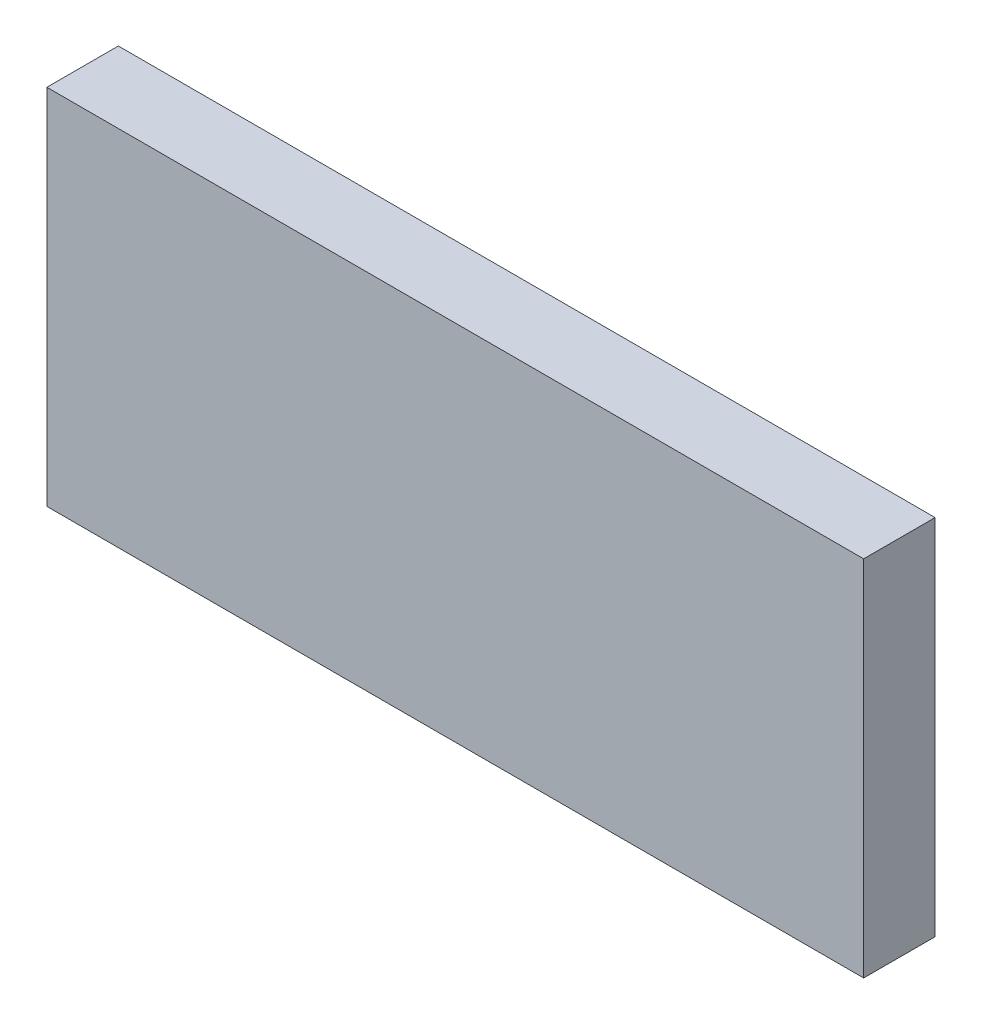
SolidWorks part; units mm, degrees
ref_plane "Ebene vorne" through (0, 0, 0) normal (0, 0, 1) x (1, 0, 0)
ref_plane "Ebene oben" through (0, 0, 0) normal (0, 1, 0) x (1, 0, 0)
ref_plane "Ebene rechts" through (0, 0, 0) normal (1, 0, 0) x (0, 0, -1)
sketch "Skizze1" plane through (0, 0, 0) normal (0, 0, 1) x (1, 0, 0)
  line L0 (-5.715, 2.54) -> (5.715, 2.54)
  line L1 (5.715, 2.54) -> (5.715, -2.54)
  line L2 (5.715, -2.54) -> (-5.715, -2.54)
  line L3 (-5.715, -2.54) -> (-5.715, 2.54)
extrude "Component_Outline" add sketch "Skizze1" along normal blind 1 separate body
sketch3d "3D-Skizze1"
  line L0 (0, 0, 0) -> (1, 0, 0)
  line L1 (0, 0, 0) -> (0, 1, 0)
  line L2 (0, 0, 0) -> (0, 0, 1)
  point P0 (0, 0, 0)
